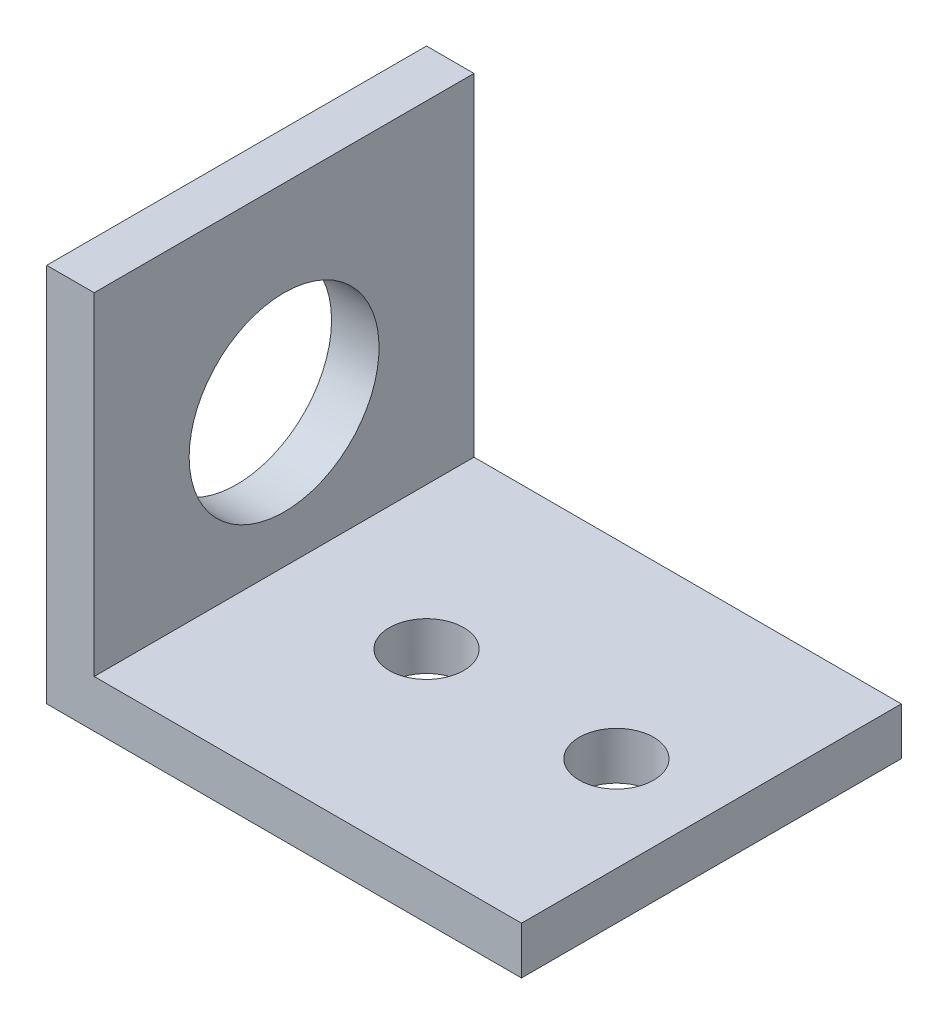
SolidWorks part; units mm, degrees
material "6061-T6 (SS)"
ref_plane "Front Plane" through (0, 0, 0) normal (0, 0, 1) x (1, 0, 0)
ref_plane "Top Plane" through (0, 0, 0) normal (0, 1, 0) x (1, 0, 0)
ref_plane "Right Plane" through (0, 0, 0) normal (1, 0, 0) x (0, 0, -1)
sketch "Sketch1" plane through (0, 0, 0) normal (0, 0, 1) x (1, 0, 0)
  line L0 (0, 0) -> (0, 25.4)
  line L1 (0, 25.4) -> (3.175, 25.4)
  line L2 (3.175, 25.4) -> (3.175, 3.175)
  line L3 (3.175, 3.175) -> (31.75, 3.175)
  line L4 (31.75, 3.175) -> (31.75, 0)
  line L5 (31.75, 0) -> (0, 0)
  dimension "D1" = 3.175
  dimension "D2" = 25.4
  dimension "D3" = 31.75
extrude "Boss-Extrude1" add sketch "Sketch1" along normal blind 25.4 contours L2 L3 L4 L5 L0 L1
sketch "Sketch2" plane through (0, 0, 0) normal (0, -1, 0) x (1, 0, 0)
  line L0 (31.75, 12.7) -> (0, 12.7) construction
  line L1 (31.75, 25.4) -> (31.75, 0) construction
  line L2 (0, 25.4) -> (0, 0) construction
  circle A0 centre (12.7, 12.7) radius 2.4892
  circle A1 centre (25.4, 12.7) radius 2.4892
  dimension "D1" = 4.9784
  dimension "D2" = 12.7
  dimension "D3" = 12.7
sketch "Sketch3" plane through (0, 0, 0) normal (-1, 0, 0) x (0, 0, 1)
  line L1 (25.4, 0) -> (0, 0) construction
  line L3 (25.4, 0) -> (25.4, 25.4) construction
  circle A1 centre (12.7, 12.7) radius 6.35
  dimension "D1" = 12.7
  dimension "D2" = 12.7
  dimension "D4" = 12.7
extrude "Cut-Extrude1" cut sketch "Sketch3" against normal through all
extrude "Cut-Extrude2" cut sketch "Sketch2" against normal through all contours A0 | A1
